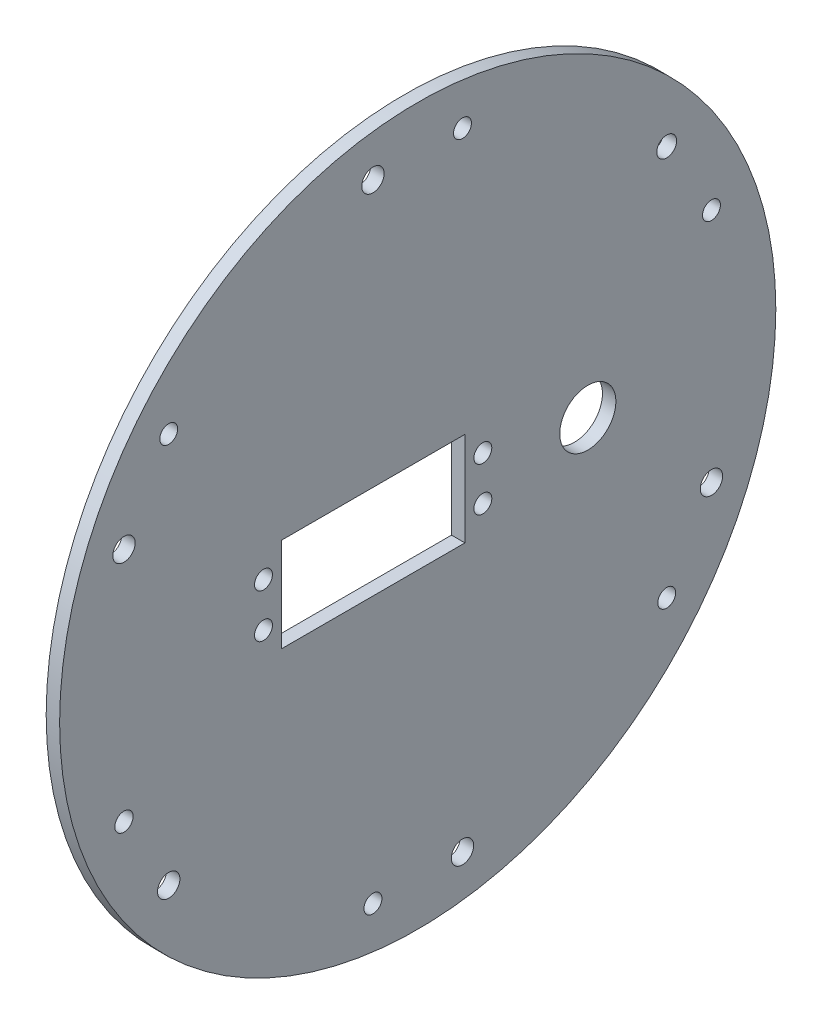
SolidWorks part; units mm, degrees
ref_plane "正面" through (0, 0, 0) normal (0, 0, 1) x (1, 0, 0)
ref_plane "平面" through (0, 0, 0) normal (0, 1, 0) x (1, 0, 0)
ref_plane "右側面" through (0, 0, 0) normal (1, 0, 0) x (0, 0, -1)
sketch "ｽｹｯﾁ1" plane through (0, 0, 0) normal (1, 0, 0) x (0, 0, -1)
  line L1 (-2457.3238, 1489.9955) -> (-2416.3238, 1489.9955)
  line L2 (-2457.3238, 1489.9955) -> (-2457.3238, 1468.9955)
  line L3 (-2457.3238, 1468.9955) -> (-2416.3238, 1468.9955)
  line L4 (-2416.3238, 1489.9955) -> (-2416.3238, 1468.9955)
  circle A0 centre (-2426.8738, 1479.4955) radius 80
  circle A1 centre (-2388.8738, 1479.4955) radius 6.27
  circle A2 centre (-2412.3238, 1484.3955) radius 2
  circle A3 centre (-2412.3238, 1474.5955) radius 2
  circle A4 centre (-2461.3238, 1484.3955) radius 2
  circle A5 centre (-2461.3238, 1474.5955) radius 2
  circle A6 centre (-2492.4955, 1505.8352) radius 2.5
  circle A7 centre (-2482.4955, 1523.1557) radius 2
  circle A8 centre (-2436.8738, 1549.4955) radius 2.5
  circle A9 centre (-2416.8738, 1549.4955) radius 2
  circle A10 centre (-2371.252, 1523.1557) radius 2.2145
  circle A11 centre (-2361.252, 1505.8352) radius 2
  circle A12 centre (-2361.252, 1453.1557) radius 2.5
  circle A13 centre (-2371.252, 1435.8352) radius 2
  circle A14 centre (-2416.8738, 1409.4955) radius 2.5
  circle A15 centre (-2436.8738, 1409.4955) radius 2
  circle A16 centre (-2482.4955, 1435.8352) radius 2.5
  circle A17 centre (-2492.4955, 1453.1557) radius 2.0395
extrude "ﾎﾞｽ - 押し出し1" add sketch "ｽｹｯﾁ1" along normal blind 3
